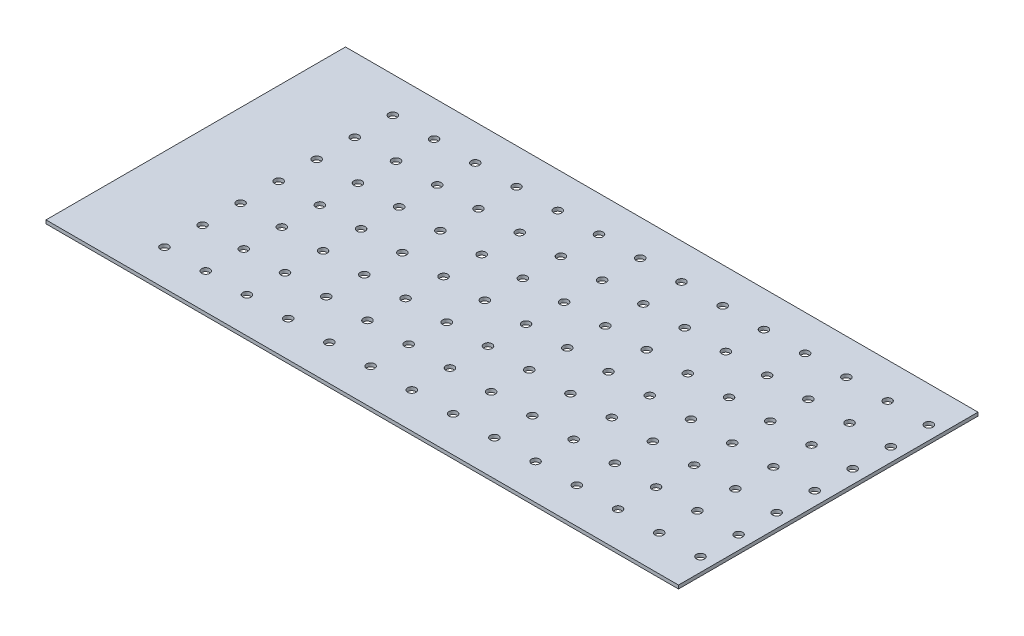
SolidWorks part; units mm, degrees
material "ABS PC"
ref_plane "Front Plane" through (0, 0, 0) normal (0, 0, 1) x (1, 0, 0)
ref_plane "Top Plane" through (0, 0, 0) normal (0, 1, 0) x (1, 0, 0)
ref_plane "Right Plane" through (0, 0, 0) normal (1, 0, 0) x (0, 0, -1)
sketch "Sketch1" plane through (0, 0, 0) normal (0, 1, 0) x (1, 0, 0)
  line L1 (-270, 129.32) -> (270, 129.32)
  line L2 (-270, 129.32) -> (-270, -129.32)
  line L3 (-270, -129.32) -> (270, -129.32)
  line L4 (270, 129.32) -> (270, -129.32)
  line L5 (-270, 129.32) -> (270, -129.32) construction
  line L6 (-270, -129.32) -> (270, 129.32) construction
  point P0 (0, 0)
  dimension "D1" = 540
  dimension "D2" = 258.64
extrude "Boss-Extrude1" add sketch "Sketch1" along normal blind 3.18
sketch "Sketch2" plane through (0, 3.18, 0) normal (0, 1, 0) x (1, 0, 0)
  line L0 (-270, 129.32) -> (-270, -129.32) construction
  line L1 (270, 129.32) -> (-270, 129.32) construction
  circle A0 centre (-234, 104.72) radius 3.75
  dimension "D1" = 7.5
  dimension "D2" = 36
  dimension "D3" = 24.6
extrude "Cut-Extrude1" cut sketch "Sketch2" against normal up to next
pattern_linear "LPattern1" count 14 spacing 37.81 along (1, 0, 0) count 7 spacing 34.9 along (0, 0, 1) of "Cut-Extrude1"
sketch "Sketch4" plane through (-270, 0, 0) normal (-1, 0, 0) x (0, 0, 1)
  line L1 (-129.32, 3.18) -> (129.32, 3.18)
  line L2 (-129.32, 3.18) -> (-129.32, 0)
  line L3 (-129.32, 0) -> (129.32, 0)
  line L4 (129.32, 3.18) -> (129.32, 0)
extrude "Boss-Extrude2" add sketch "Sketch4" along normal blind 40
sketch "Sketch5" plane through (0, 0, 129.32) normal (0, 0, 1) x (1, 0, 0)
  line L1 (270, 3.18) -> (-310, 3.18)
  line L2 (270, 3.18) -> (270, 0)
  line L3 (270, 0) -> (-310, 0)
  line L4 (-310, 3.18) -> (-310, 0)
extrude "Boss-Extrude3" add sketch "Sketch5" along normal blind 8
mirror "Mirror1" about plane through (0, 0, 0) normal (0, 0, 1) of "Boss-Extrude3"
